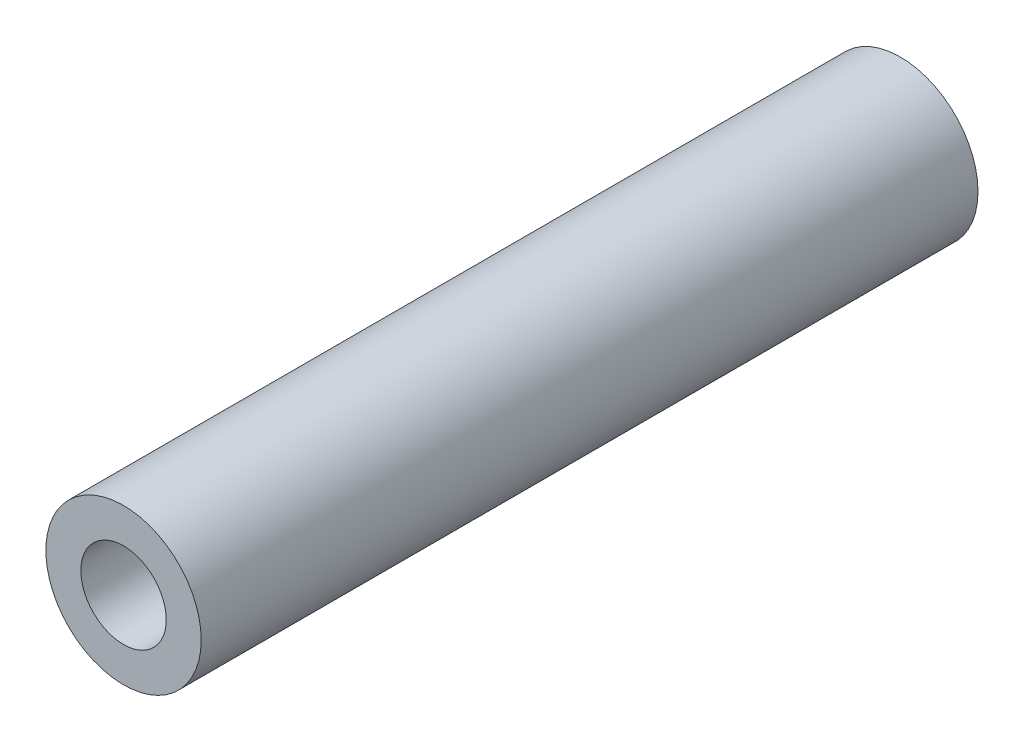
SolidWorks part; units mm, degrees
ref_plane "Front Plane" through (0, 0, 0) normal (0, 0, 1) x (1, 0, 0)
ref_plane "Top Plane" through (0, 0, 0) normal (0, 1, 0) x (1, 0, 0)
ref_plane "Right Plane" through (0, 0, 0) normal (1, 0, 0) x (0, 0, -1)
sketch "Sketch1" plane through (0, 0, 0) normal (0, 0, 1) x (1, 0, 0)
  circle A0 centre (0, 0) radius 1.65
  circle A1 centre (0, 0) radius 3
  dimension "D1" = 3.3
  dimension "D2" = 6
extrude "Boss-Extrude1" add sketch "Sketch1" along normal mid plane 30
